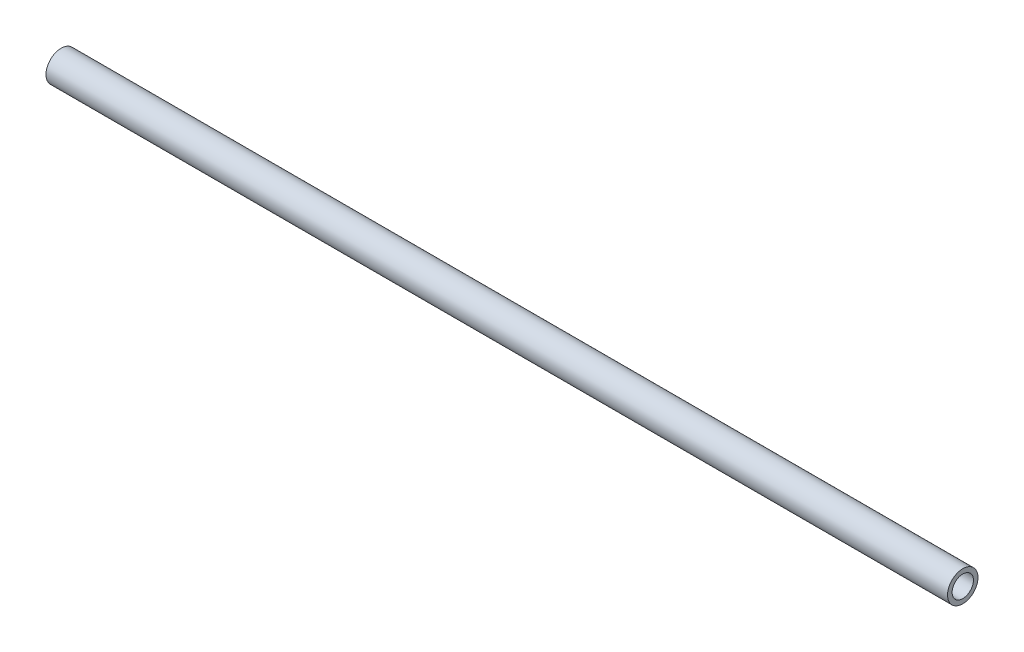
SolidWorks part; units mm, degrees
material "6061-T6 (SS)"
ref_plane "Front Plane" through (0, 0, 0) normal (0, 0, 1) x (1, 0, 0)
ref_plane "Top Plane" through (0, 0, 0) normal (0, 1, 0) x (1, 0, 0)
ref_plane "Right Plane" through (0, 0, 0) normal (1, 0, 0) x (0, 0, -1)
sketch "Sketch1" plane through (0, 0, 0) normal (1, 0, 0) x (0, 0, -1)
  circle A0 centre (0, 0) radius 15.875
  circle A1 centre (0, 0) radius 11.1125
  dimension "D1" = 31.75
  dimension "D2" = 4.7625
extrude "Boss-Extrude1" add sketch "Sketch1" along normal blind 939.8
